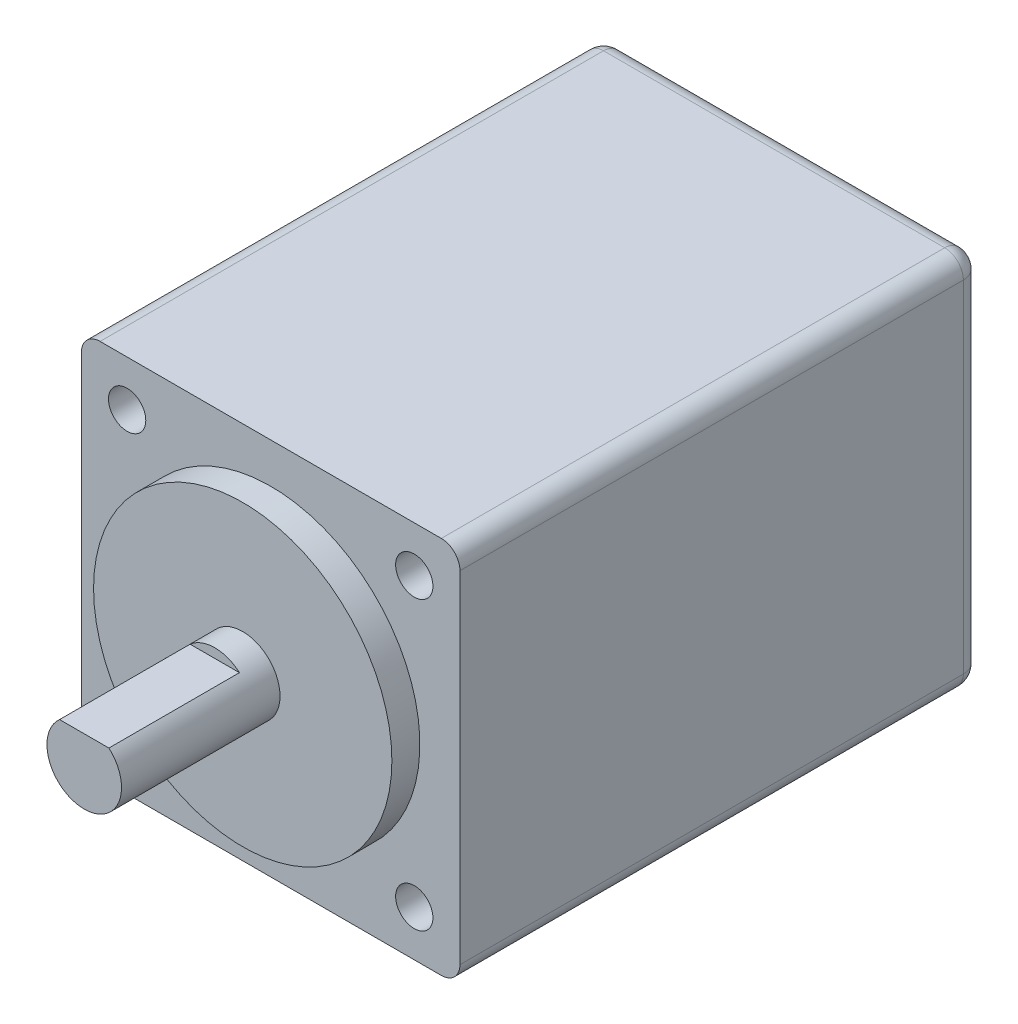
SolidWorks part; units mm, degrees
ref_plane "Front Plane" through (0, 0, 0) normal (0, 0, 1) x (1, 0, 0)
ref_plane "Top Plane" through (0, 0, 0) normal (0, 1, 0) x (1, 0, 0)
ref_plane "Right Plane" through (0, 0, 0) normal (1, 0, 0) x (0, 0, -1)
sketch "Sketch1" plane through (0, 0, 0) normal (0, 0, 1) x (1, 0, 0)
  line L1 (-10.15, -10.15) -> (10.15, -10.15)
  line L2 (-10.15, -10.15) -> (-10.15, 10.15)
  line L3 (-10.15, 10.15) -> (10.15, 10.15)
  line L4 (10.15, -10.15) -> (10.15, 10.15)
  line L5 (-10.15, -10.15) -> (10.15, 10.15) construction
  line L6 (-10.15, 10.15) -> (10.15, -10.15) construction
  point P0 (0, 0)
  dimension "D1" = 20.3
  dimension "D2" = 20.3
extrude "Boss-Extrude1" add sketch "Sketch1" along normal blind 28
sketch "Sketch2" plane through (0, 0, 28) normal (0, 0, 1) x (1, 0, 0)
  circle A0 centre (0, 0) radius 8
  dimension "D1" = 16
extrude "Boss-Extrude2" add sketch "Sketch2" along normal blind 1.5
sketch "Sketch3" plane through (0, 0, 29.5) normal (0, 0, 1) x (1, 0, 0)
  circle A0 centre (0, 0) radius 2
  dimension "D1" = 4
extrude "Boss-Extrude3" add sketch "Sketch3" along normal blind 8.5
sketch "Sketch4" plane through (0, 0, 0) normal (1, 0, 0) x (0, 0, -1)
  line L1 (-38, 2) -> (-31, 2)
  line L2 (-38, 2) -> (-38, 1.5)
  line L3 (-38, 1.5) -> (-31, 1.5)
  line L4 (-31, 2) -> (-31, 1.5)
  dimension "D1" = 7
  dimension "D2" = 0.5
extrude "Cut-Extrude1" cut sketch "Sketch4" against normal mid plane 10
sketch "Sketch5" plane through (0, 0, 28) normal (0, 0, 1) x (1, 0, 0)
  line L1 (-7.7, -7.7) -> (7.7, -7.7) construction
  line L2 (-7.7, -7.7) -> (-7.7, 7.7) construction
  line L3 (-7.7, 7.7) -> (7.7, 7.7) construction
  line L4 (7.7, -7.7) -> (7.7, 7.7) construction
  line L5 (-7.7, -7.7) -> (7.7, 7.7) construction
  line L6 (-7.7, 7.7) -> (7.7, -7.7) construction
  circle A0 centre (-7.7, 7.7) radius 1
  circle A1 centre (7.7, 7.7) radius 1
  circle A2 centre (7.7, -7.7) radius 1
  circle A3 centre (-7.7, -7.7) radius 1
  point P0 (0, 0)
  dimension "D3" = 2
  dimension "D1" = 15.4
  dimension "D2" = 15.4
  dimension "D4" = 4
extrude "Cut-Extrude2" cut sketch "Sketch5" against normal blind 2.5
fillet "Fillet1" radius 1 8 edges at (0, 10.15, 0) (-10.15, 0, 0) (0, -10.15, 0) (10.15, 0, 0) (-10.15, -10.15, 14) (10.15, -10.15, 14) (-10.15, 10.15, 14) (10.15, 10.15, 14)
